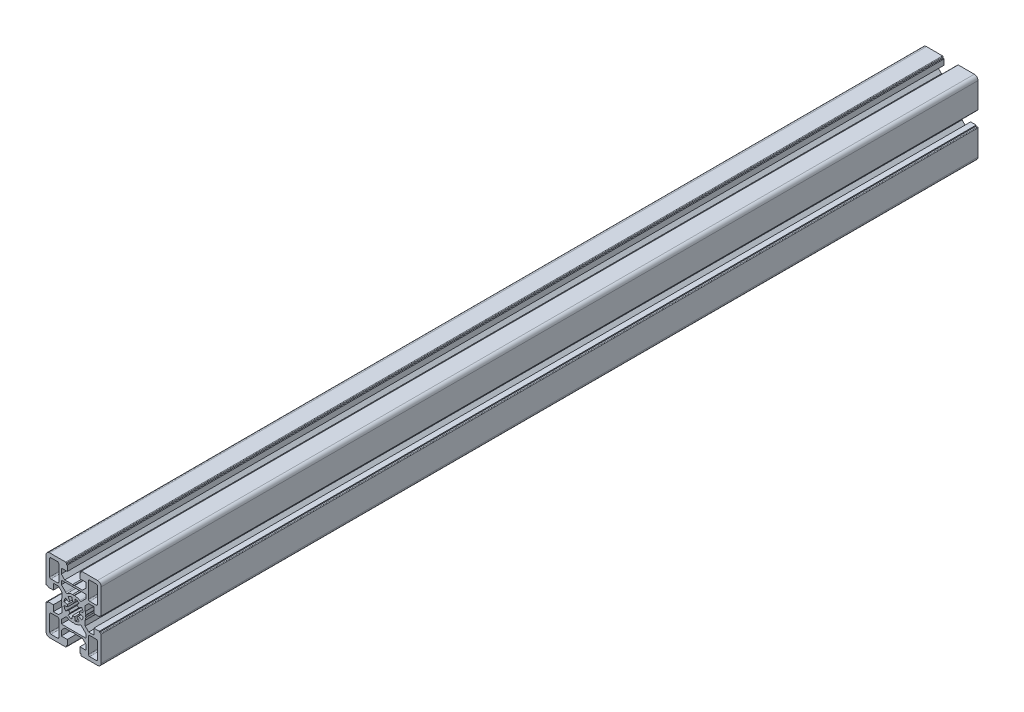
SolidWorks part; units mm, degrees
ref_plane "Спереди" through (0, 0, 0) normal (0, 0, 1) x (1, 0, 0)
ref_plane "Сверху" through (0, 0, 0) normal (0, 1, 0) x (1, 0, 0)
ref_plane "Справа" through (0, 0, 0) normal (1, 0, 0) x (0, 0, -1)
sketch "Model" plane through (0, 0, 0) normal (0, 0, 1) x (1, 0, 0)
  line L118 (-12.0501, -13.05) -> (-12.0501, -26)
  line L119 (-13.0501, -27) -> (-18.5001, -27)
  line L120 (-19.5001, -26) -> (-19.5001, -13.05)
  line L121 (-18.5001, -12.05) -> (-13.0501, -12.05)
  line L122 (-1.3892, 7.8785) -> (-0.8683, 4.924)
  line L123 (0.8682, 4.924) -> (1.3891, 7.8785)
  line L124 (4.5886, 6.5532) -> (2.8678, 4.0958)
  line L125 (4.0957, 2.8679) -> (6.5532, 4.5886)
  line L126 (7.8784, 1.3892) -> (4.924, 0.8682)
  line L127 (4.924, -0.8682) -> (7.8784, -1.3892)
  line L128 (6.5532, -4.5886) -> (4.0957, -2.8679)
  line L129 (2.8678, -4.0958) -> (4.5886, -6.5532)
  line L130 (1.3891, -7.8785) -> (0.8682, -4.924)
  line L131 (-0.8683, -4.924) -> (-1.3892, -7.8785)
  line L132 (-4.5887, -6.5532) -> (-2.8679, -4.0958)
  line L133 (-4.0958, -2.8679) -> (-6.5533, -4.5886)
  line L134 (-7.8785, -1.3892) -> (-4.9241, -0.8682)
  line L135 (-4.9241, 0.8682) -> (-7.8785, 1.3892)
  line L136 (-6.5533, 4.5886) -> (-4.0958, 2.8679)
  line L137 (-2.8679, 4.0958) -> (-4.5887, 6.5532)
  line L138 (-12.0501, 26) -> (-12.0501, 13.05)
  line L139 (-13.0501, 12.05) -> (-18.5001, 12.05)
  line L140 (-19.5001, 13.05) -> (-19.5001, 26)
  line L141 (-18.5001, 27) -> (-13.0501, 27)
  line L142 (0.8092, 9.9672) -> (-0.0001, 9.5)
  line L143 (-0.0001, 9.5) -> (-0.8093, 9.9672)
  line L144 (-6.4186, 8.6939) -> (-10.0001, 12.2754)
  line L145 (-10.0001, 12.2754) -> (-10.0001, 15.5)
  line L146 (-10.0001, 15.5) -> (9.9999, 15.5)
  line L147 (9.9999, 15.5) -> (9.9999, 12.2754)
  line L148 (9.9999, 12.2754) -> (6.4184, 8.6939)
  line L149 (13.05, 27) -> (18.4999, 27)
  line L150 (19.4999, 26) -> (19.4999, 13.05)
  line L151 (18.4999, 12.05) -> (13.05, 12.05)
  line L152 (12.05, 13.05) -> (12.05, 26)
  line L153 (6.4184, -8.6939) -> (9.9999, -12.2754)
  line L154 (9.9999, -12.2754) -> (9.9999, -15.5)
  line L155 (9.9999, -15.5) -> (-10.0001, -15.5)
  line L156 (-10.0001, -15.5) -> (-10.0001, -12.2754)
  line L157 (-10.0001, -12.2754) -> (-6.4186, -8.6939)
  line L158 (-0.8093, -9.9672) -> (-0.0001, -9.5)
  line L159 (-0.0001, -9.5) -> (0.8092, -9.9672)
  line L160 (19.4999, -13.05) -> (19.4999, -26)
  line L161 (18.4999, -27) -> (13.05, -27)
  line L162 (12.05, -26) -> (12.05, -13.05)
  line L163 (13.05, -12.05) -> (18.4999, -12.05)
  line L164 (22.4999, 6.45) -> (22.4999, 27)
  line L165 (19.4999, 30) -> (6.4499, 30)
  line L166 (5.9499, 29.5) -> (5.9499, 28.5)
  line L167 (5.9499, 28.5) -> (5.1499, 28.5)
  line L168 (5.1499, 28.5) -> (5.1499, 23.9999)
  line L169 (5.1499, 23.9999) -> (10.0499, 23.9999)
  line L170 (10.0499, 23.9999) -> (10.0499, 19.7999)
  line L171 (10.0499, 19.7999) -> (7.25, 17)
  line L172 (7.25, 17) -> (0.8092, 17)
  line L173 (0.8092, 17) -> (-0.0001, 16.5328)
  line L174 (-0.0001, 16.5328) -> (-0.8093, 17)
  line L175 (-0.8093, 17) -> (-7.2501, 17)
  line L176 (-7.2501, 17) -> (-10.0501, 19.8)
  line L177 (-10.0501, 19.8) -> (-10.0501, 23.9999)
  line L178 (-10.0501, 23.9999) -> (-5.1501, 23.9999)
  line L179 (-5.1501, 23.9999) -> (-5.1501, 28.5)
  line L180 (-5.1501, 28.5) -> (-5.9501, 28.5)
  line L181 (-5.9501, 28.5) -> (-5.9501, 29.5)
  line L182 (-6.4501, 30) -> (-19.5001, 30)
  line L183 (-22.5001, 27) -> (-22.5001, 6.45)
  line L184 (-22.0001, 5.95) -> (-21.0002, 5.95)
  line L185 (-21.0002, 5.95) -> (-21.0002, 5.15)
  line L186 (-21.0002, 5.15) -> (-16.5001, 5.15)
  line L187 (-16.5001, 5.15) -> (-16.5001, 10.05)
  line L188 (-16.5001, 10.05) -> (-12.3001, 10.05)
  line L189 (-12.3001, 10.05) -> (-9.5001, 7.2499)
  line L190 (-9.5001, 7.2499) -> (-9.5001, 3.1225)
  line L191 (-9.9673, 0.8093) -> (-9.5, 0)
  line L192 (-9.5, 0) -> (-9.9673, -0.8093)
  line L193 (-9.5001, -3.1225) -> (-9.5001, -7.2499)
  line L194 (-9.5001, -7.2499) -> (-12.3001, -10.05)
  line L195 (-12.3001, -10.05) -> (-16.5001, -10.05)
  line L196 (-16.5001, -10.05) -> (-16.5001, -5.15)
  line L197 (-16.5001, -5.15) -> (-21.0002, -5.15)
  line L198 (-21.0002, -5.15) -> (-21.0002, -5.95)
  line L199 (-21.0002, -5.95) -> (-22.0001, -5.95)
  line L200 (-22.5001, -6.45) -> (-22.5001, -27)
  line L201 (-19.5001, -30) -> (-6.4501, -30)
  line L202 (-5.9501, -29.5) -> (-5.9501, -28.5)
  line L203 (-5.9501, -28.5) -> (-5.1501, -28.5)
  line L204 (-5.1501, -28.5) -> (-5.1501, -23.9999)
  line L205 (-5.1501, -23.9999) -> (-10.0501, -23.9999)
  line L206 (-10.0501, -23.9999) -> (-10.0501, -19.8)
  line L207 (-10.0501, -19.8) -> (-7.2501, -17)
  line L208 (-7.2501, -17) -> (-0.8093, -17)
  line L209 (-0.8093, -17) -> (-0.0001, -16.5328)
  line L210 (-0.0001, -16.5328) -> (0.8092, -17)
  line L211 (0.8092, -17) -> (7.25, -17)
  line L212 (7.25, -17) -> (10.0499, -19.7999)
  line L213 (10.0499, -19.7999) -> (10.0499, -23.9999)
  line L214 (10.0499, -23.9999) -> (5.1499, -23.9999)
  line L215 (5.1499, -23.9999) -> (5.1499, -28.5)
  line L216 (5.1499, -28.5) -> (5.9499, -28.5)
  line L217 (5.9499, -28.5) -> (5.9499, -29.5)
  line L218 (6.4499, -30) -> (19.4999, -30)
  line L219 (22.4999, -27) -> (22.4999, -6.45)
  line L220 (21.9999, -5.95) -> (21.0001, -5.95)
  line L221 (21.0001, -5.95) -> (21.0001, -5.15)
  line L222 (21.0001, -5.15) -> (16.5, -5.15)
  line L223 (16.5, -5.15) -> (16.5, -10.05)
  line L224 (16.5, -10.05) -> (12.3, -10.05)
  line L225 (12.3, -10.05) -> (9.5, -7.2499)
  line L226 (9.5, -7.2499) -> (9.5, -3.1225)
  line L227 (9.9672, -0.8093) -> (9.4999, 0)
  line L228 (9.4999, 0) -> (9.9672, 0.8093)
  line L229 (9.5, 3.1225) -> (9.5, 7.2499)
  line L230 (9.5, 7.2499) -> (12.3, 10.05)
  line L231 (12.3, 10.05) -> (16.5, 10.05)
  line L232 (16.5, 10.05) -> (16.5, 5.15)
  line L233 (16.5, 5.15) -> (21.0001, 5.15)
  line L234 (21.0001, 5.15) -> (21.0001, 5.95)
  line L235 (21.0001, 5.95) -> (21.9999, 5.95)
  arc A56 (-13.0501, -27) -> (-12.0501, -26) centre (-13.0501, -26) ccw
  arc A57 (-19.5001, -26) -> (-18.5001, -27) centre (-18.5001, -26) ccw
  arc A58 (-18.5001, -12.05) -> (-19.5001, -13.05) centre (-18.5001, -13.05) ccw
  arc A59 (-12.0501, -13.05) -> (-13.0501, -12.05) centre (-13.0501, -13.05) ccw
  arc A60 (-1.3892, 7.8785) -> (-4.5887, 6.5532) centre (-0.0001, 0) ccw
  arc A61 (0.8682, 4.924) -> (-0.8683, 4.924) centre (-0.0001, 0) ccw
  arc A62 (4.5886, 6.5532) -> (1.3891, 7.8785) centre (-0.0001, 0) ccw
  arc A63 (4.0957, 2.8679) -> (2.8678, 4.0958) centre (-0.0001, 0) ccw
  arc A64 (7.8784, 1.3892) -> (6.5532, 4.5886) centre (-0.0001, 0) ccw
  arc A65 (4.924, -0.8682) -> (4.924, 0.8682) centre (-0.0001, 0) ccw
  arc A66 (6.5532, -4.5886) -> (7.8784, -1.3892) centre (-0.0001, 0) ccw
  arc A67 (2.8678, -4.0958) -> (4.0957, -2.8679) centre (-0.0001, 0) ccw
  arc A68 (1.3891, -7.8785) -> (4.5886, -6.5532) centre (-0.0001, 0) ccw
  arc A69 (-0.8683, -4.924) -> (0.8682, -4.924) centre (-0.0001, 0) ccw
  arc A70 (-4.5887, -6.5532) -> (-1.3892, -7.8785) centre (-0.0001, 0) ccw
  arc A71 (-4.0958, -2.8679) -> (-2.8679, -4.0958) centre (-0.0001, 0) ccw
  arc A72 (-7.8785, -1.3892) -> (-6.5533, -4.5886) centre (-0.0001, 0) ccw
  arc A73 (-4.9241, 0.8682) -> (-4.9241, -0.8682) centre (-0.0001, 0) ccw
  arc A74 (-6.5533, 4.5886) -> (-7.8785, 1.3892) centre (-0.0001, 0) ccw
  arc A75 (-2.8679, 4.0958) -> (-4.0958, 2.8679) centre (-0.0001, 0) ccw
  arc A76 (-12.0501, 26) -> (-13.0501, 27) centre (-13.0501, 26) ccw
  arc A77 (-13.0501, 12.05) -> (-12.0501, 13.05) centre (-13.0501, 13.05) ccw
  arc A78 (-19.5001, 13.05) -> (-18.5001, 12.05) centre (-18.5001, 13.05) ccw
  arc A79 (-18.5001, 27) -> (-19.5001, 26) centre (-18.5001, 26) ccw
  arc A80 (5.1921, 8.5464) -> (6.4184, 8.6939) centre (5.7113, 9.401) ccw
  arc A81 (5.1921, 8.5464) -> (0.8092, 9.9672) centre (-0.0001, 0) ccw
  arc A82 (-0.8093, 9.9672) -> (-5.1922, 8.5464) centre (-0.0001, 0) ccw
  arc A83 (-6.4186, 8.6939) -> (-5.1922, 8.5464) centre (-5.7115, 9.401) ccw
  arc A84 (19.4999, 26) -> (18.4999, 27) centre (18.4999, 26) ccw
  arc A85 (18.4999, 12.05) -> (19.4999, 13.05) centre (18.4999, 13.05) ccw
  arc A86 (12.05, 13.05) -> (13.05, 12.05) centre (13.05, 13.05) ccw
  arc A87 (13.05, 27) -> (12.05, 26) centre (13.05, 26) ccw
  arc A88 (-5.1922, -8.5464) -> (-6.4186, -8.6939) centre (-5.7115, -9.401) ccw
  arc A89 (-5.1922, -8.5464) -> (-0.8093, -9.9672) centre (-0.0001, 0) ccw
  arc A90 (0.8092, -9.9672) -> (5.1921, -8.5464) centre (-0.0001, 0) ccw
  arc A91 (6.4184, -8.6939) -> (5.1921, -8.5464) centre (5.7113, -9.401) ccw
  arc A92 (18.4999, -27) -> (19.4999, -26) centre (18.4999, -26) ccw
  arc A93 (12.05, -26) -> (13.05, -27) centre (13.05, -26) ccw
  arc A94 (13.05, -12.05) -> (12.05, -13.05) centre (13.05, -13.05) ccw
  arc A95 (19.4999, -13.05) -> (18.4999, -12.05) centre (18.4999, -13.05) ccw
  arc A96 (22.4999, 27) -> (19.4999, 30) centre (19.4999, 27) ccw
  arc A97 (6.4499, 30) -> (5.9499, 29.5) centre (6.4499, 29.5) ccw
  arc A98 (-5.9501, 29.5) -> (-6.4501, 30) centre (-6.4501, 29.5) ccw
  arc A99 (-19.5001, 30) -> (-22.5001, 27) centre (-19.5001, 27) ccw
  arc A100 (-22.5001, 6.45) -> (-22.0001, 5.95) centre (-22.0001, 6.45) ccw
  arc A101 (-9.5001, 3.1225) -> (-9.9673, 0.8093) centre (-0.0001, 0) ccw
  arc A102 (-9.9673, -0.8093) -> (-9.5001, -3.1225) centre (-0.0001, 0) ccw
  arc A103 (-22.0001, -5.95) -> (-22.5001, -6.45) centre (-22.0001, -6.45) ccw
  arc A104 (-22.5001, -27) -> (-19.5001, -30) centre (-19.5001, -27) ccw
  arc A105 (-6.4501, -30) -> (-5.9501, -29.5) centre (-6.4501, -29.5) ccw
  arc A106 (5.9499, -29.5) -> (6.4499, -30) centre (6.4499, -29.5) ccw
  arc A107 (19.4999, -30) -> (22.4999, -27) centre (19.4999, -27) ccw
  arc A108 (22.4999, -6.45) -> (21.9999, -5.95) centre (21.9999, -6.45) ccw
  arc A109 (9.5, -3.1225) -> (9.9672, -0.8093) centre (0, 0) ccw
  arc A110 (9.9672, 0.8093) -> (9.5, 3.1225) centre (0, 0) ccw
  arc A111 (21.9999, 5.95) -> (22.4999, 6.45) centre (21.9999, 6.45) ccw
extrude "Бобышка-Вытянуть1" add sketch "Model" along normal blind 715
